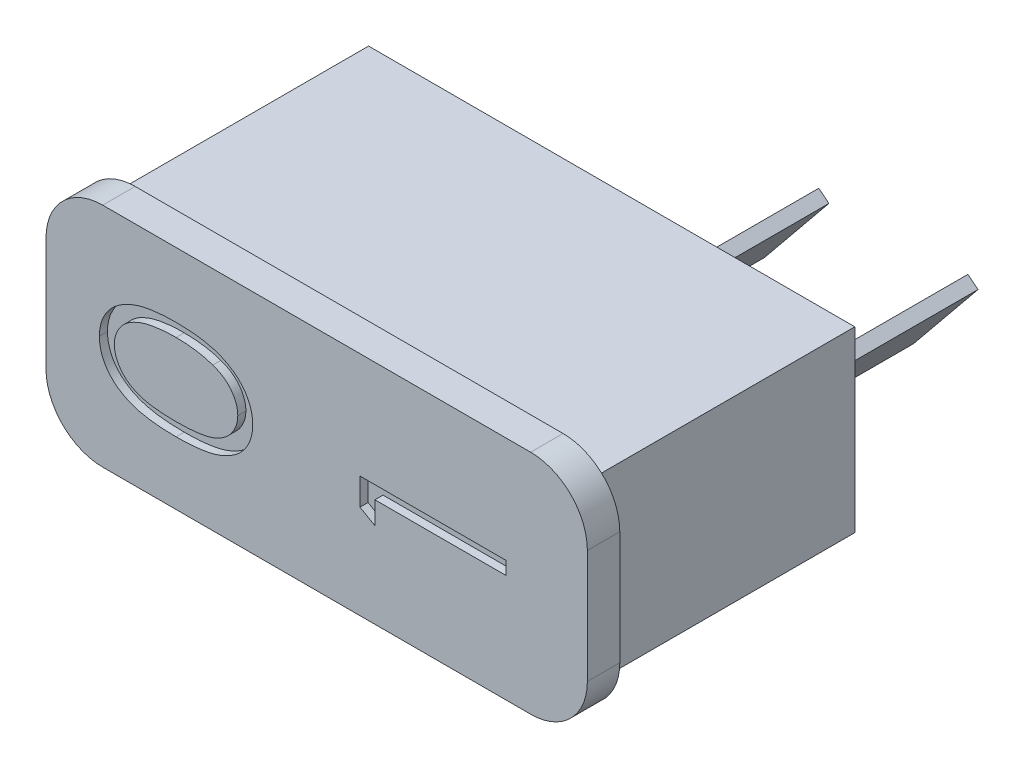
SolidWorks part; units mm, degrees
ref_plane "Plan de face" through (0, 0, 0) normal (0, 0, 1) x (1, 0, 0)
ref_plane "Plan de dessus" through (0, 0, 0) normal (0, 1, 0) x (1, 0, 0)
ref_plane "Plan de droite" through (0, 0, 0) normal (1, 0, 0) x (0, 0, -1)
sketch "Esquisse1" plane through (0, 0, 0) normal (0, 0, 1) x (1, 0, 0)
  line L1 (-15, -5.5) -> (15, -5.5)
  line L2 (-15, -5.5) -> (-15, 5.5)
  line L3 (-15, 5.5) -> (15, 5.5)
  line L4 (15, -5.5) -> (15, 5.5)
  line L5 (-15, -5.5) -> (15, 5.5) construction
  line L6 (-15, 5.5) -> (15, -5.5) construction
  point P0 (0, 0)
  dimension "D1" = 11
  dimension "D2" = 30
extrude "Boss.-Extru.1" add sketch "Esquisse1" along normal blind 16.2
sketch "Esquisse2" plane through (0, 0, 0) normal (0, 0, -1) x (-1, 0, 0)
  line L0 (-9.5202, -2.6946) -> (-13.5, 2.1892)
  line L1 (-9.5202, -2.6946) -> (-8.9, -2.1892)
  line L2 (-13.5, 2.1892) -> (-12.8798, 2.6946)
  line L3 (-8.9, -2.1892) -> (-12.8798, 2.6946)
  line L4 (-9.5202, -2.6946) -> (-12.8798, 2.6946) construction
  line L5 (-13.5, 2.1892) -> (-8.9, -2.1892) construction
  line L6 (-0.3202, -2.6946) -> (-4.3, 2.1892)
  line L7 (-0.3202, -2.6946) -> (0.3, -2.1892)
  line L8 (-4.3, 2.1892) -> (-3.6798, 2.6946)
  line L9 (0.3, -2.1892) -> (-3.6798, 2.6946)
  line L10 (-0.3202, -2.6946) -> (-3.6798, 2.6946) construction
  line L11 (-4.3, 2.1892) -> (0.3, -2.1892) construction
  line L12 (13.5, -2.1892) -> (9.5202, 2.6946) construction
  line L13 (13.5, -2.1892) -> (12.8798, -2.6946) construction
  line L14 (9.5202, 2.6946) -> (8.9, 2.1892) construction
  line L15 (12.8798, -2.6946) -> (8.9, 2.1892) construction
  line L16 (13.5, -2.1892) -> (8.9, 2.1892) construction
  line L17 (9.5202, 2.6946) -> (12.8798, -2.6946) construction
  line L18 (-15, 0) -> (15, 0) construction
  line L19 (-15, -5.5) -> (-15, 5.5) construction
  line L20 (15, 5.5) -> (15, -5.5) construction
  point P1 (-11.2, 0)
  point P2 (-2, 0)
  point P3 (11.2, 0)
  dimension "D1" = 9.2
  dimension "D2" = 13.2
  dimension "D3" = 6.3
  dimension "D4" = 0.8
  dimension "D5" = 1.5
  dimension "D6" = 1.5
extrude "Boss.-Extru.2" add sketch "Esquisse2" along normal blind 9.1
sketch "Esquisse3" plane through (0, 0, 16.2) normal (0, 0, 1) x (1, 0, 0)
  line L1 (-16.7, -7) -> (16.7, -7)
  line L2 (-16.7, -7) -> (-16.7, 7)
  line L3 (-16.7, 7) -> (16.7, 7)
  line L4 (16.7, -7) -> (16.7, 7)
  line L5 (-16.7, -7) -> (16.7, 7) construction
  line L6 (-16.7, 7) -> (16.7, -7) construction
  point P0 (0, 0)
  dimension "D1" = 14
  dimension "D2" = 33.4
extrude "Boss.-Extru.3" add sketch "Esquisse3" along normal blind 2
fillet "Congé1" radius 3.5 4 edges at (-16.7, 7, 17.2) (16.7, 7, 17.2) (16.7, -7, 17.2) (-16.7, -7, 17.2)
sketch "Esquisse5" plane through (0, 0, 18.2) normal (0, 0, 1) x (1, 0, 0)
  line L0 (-4.1759, -7) -> (-4.1759, 7) construction
  line L1 (-13.2, -7) -> (13.2, -7) construction
  line L2 (13.2, 7) -> (-13.2, 7) construction
  text T0 "0\r\n1" font "Century Gothic" height 9
extrude "Enlèv. mat.-Extru.1" cut sketch "Esquisse5" against normal blind 0.5
